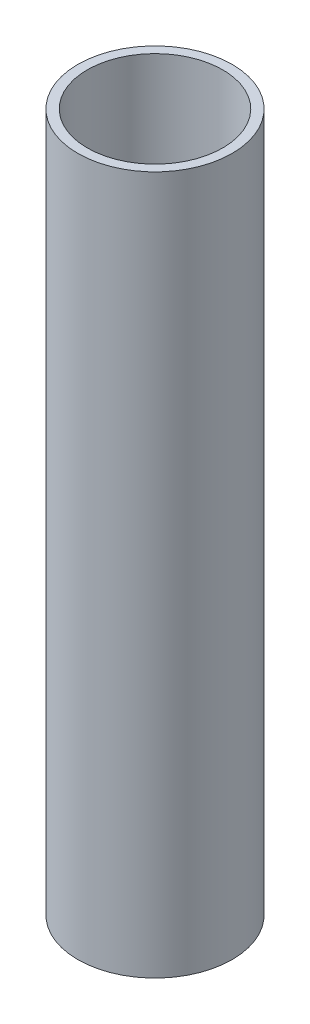
SolidWorks part; units mm, degrees
ref_plane "Front Plane" through (0, 0, 0) normal (0, 0, 1) x (1, 0, 0)
ref_plane "Top Plane" through (0, 0, 0) normal (0, 1, 0) x (1, 0, 0)
ref_plane "Right Plane" through (0, 0, 0) normal (1, 0, 0) x (0, 0, -1)
sketch "Sketch1" plane through (0, 0, 0) normal (0, 1, 0) x (1, 0, 0)
  circle A0 centre (0, 0) radius 9.7
  circle A1 centre (0, 0) radius 11.05
extrude "Boss-Extrude1" add sketch "Sketch1" along normal blind 100
